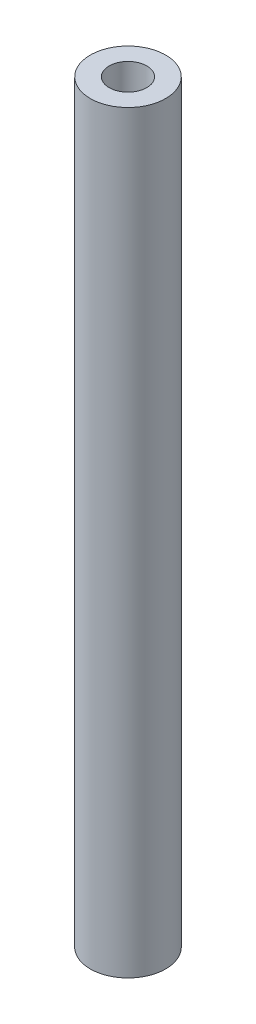
SolidWorks part; units mm, degrees
ref_plane "Alzado" through (0, 0, 0) normal (0, 0, 1) x (1, 0, 0)
ref_plane "Planta" through (0, 0, 0) normal (0, 1, 0) x (1, 0, 0)
ref_plane "Vista lateral" through (0, 0, 0) normal (1, 0, 0) x (0, 0, -1)
sketch "Croquis base" plane through (0, 0, 0) normal (0, 1, 0) x (1, 0, 0)
  circle A0 centre (0, 0) radius 2.5
  dimension "D1" = 5
extrude "Saliente-Extruir1" add sketch "Croquis base" along normal blind 50
sketch "Croquis barreno" plane through (0, 50, 0) normal (0, 1, 0) x (1, 0, 0)
  circle A0 centre (0, 0) radius 1.25
  dimension "D1" = 2.5
extrude "Cortar-Extruir1" cut sketch "Croquis barreno" against normal through all
